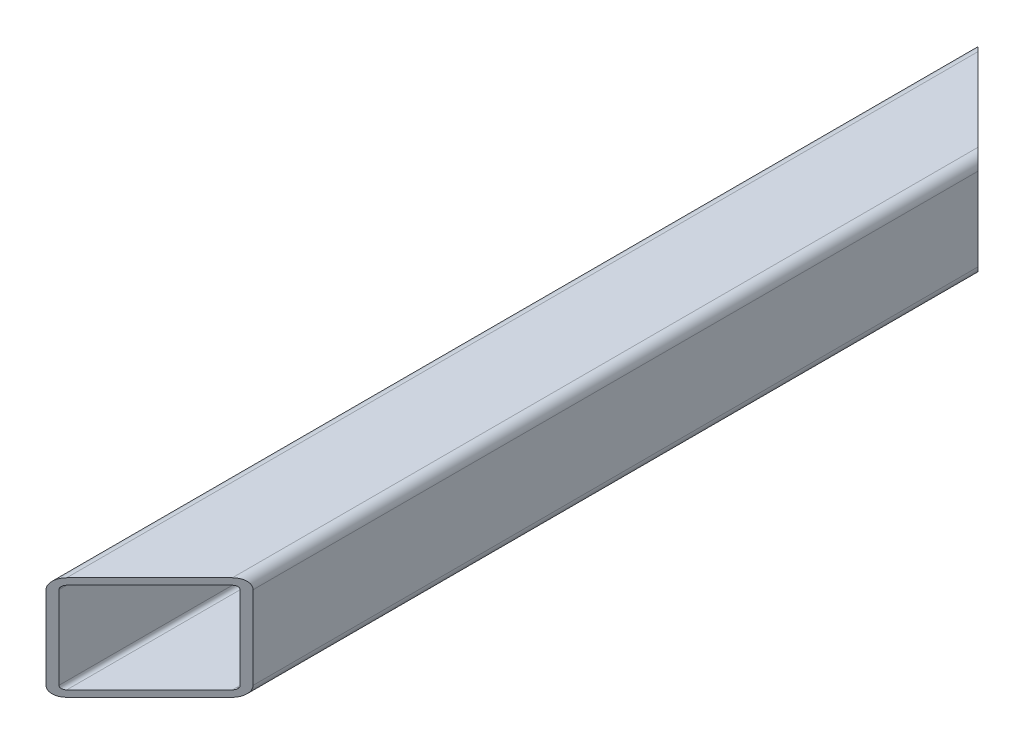
SolidWorks part; units mm, degrees
material "1.0037 (S235JR)"
ref_plane "Płaszczyzna przednia" through (0, 0, 0) normal (0, 0, 1) x (1, 0, 0)
ref_plane "Płaszczyzna górna" through (0, 0, 0) normal (0, 1, 0) x (1, 0, 0)
ref_plane "Płaszczyzna prawa" through (0, 0, 0) normal (1, 0, 0) x (0, 0, -1)
sketch "Szkic1" plane through (0, 0, 0) normal (0, 0, 1) x (1, 0, 0)
  line L0 (5, 8) -> (5, 72)
  line L1 (8, 0) -> (72, 0)
  line L2 (0, 8) -> (0, 72)
  line L3 (8, 80) -> (72, 80)
  line L4 (80, 8) -> (80, 72)
  line L5 (8, 75) -> (72, 75)
  line L6 (75, 8) -> (75, 72)
  line L7 (8, 5) -> (72, 5)
  arc A0 (8, 0) -> (0, 8) centre (8, 8) cw
  arc A1 (72, 0) -> (80, 8) centre (72, 8) ccw
  arc A2 (80, 72) -> (72, 80) centre (72, 72) ccw
  arc A3 (8, 80) -> (0, 72) centre (8, 72) ccw
  arc A4 (8, 75) -> (5, 72) centre (8, 72) ccw
  arc A5 (75, 72) -> (72, 75) centre (72, 72) ccw
  arc A6 (72, 5) -> (75, 8) centre (72, 8) ccw
  arc A7 (8, 5) -> (5, 8) centre (8, 8) cw
  point P7 (0, 0)
  point P14 (0, 80)
  dimension "D2" = 8
  dimension "D1" = 80
  dimension "D3" = 5
extrude "Dodanie-wyciągnięcie1" add sketch "Szkic1" against normal blind 720
sketch "Szkic2" plane through (0, 80, 0) normal (0, 1, 0) x (1, 0, 0)
  line L0 (0, 360) -> (80, 360) construction
  line L1 (0, 720) -> (0, 0) construction
  line L2 (80, 720) -> (80, 0) construction
  line L3 (0, 0) -> (80, 0)
  line L4 (80, 0) -> (80, 80)
  line L5 (80, 80) -> (0, 0)
  line L6 (80, 640) -> (0, 720)
  line L7 (80, 720) -> (80, 640)
  line L8 (0, 720) -> (80, 720)
extrude "Wytnij-wyciągnięcie1" cut sketch "Szkic2" against normal through all
